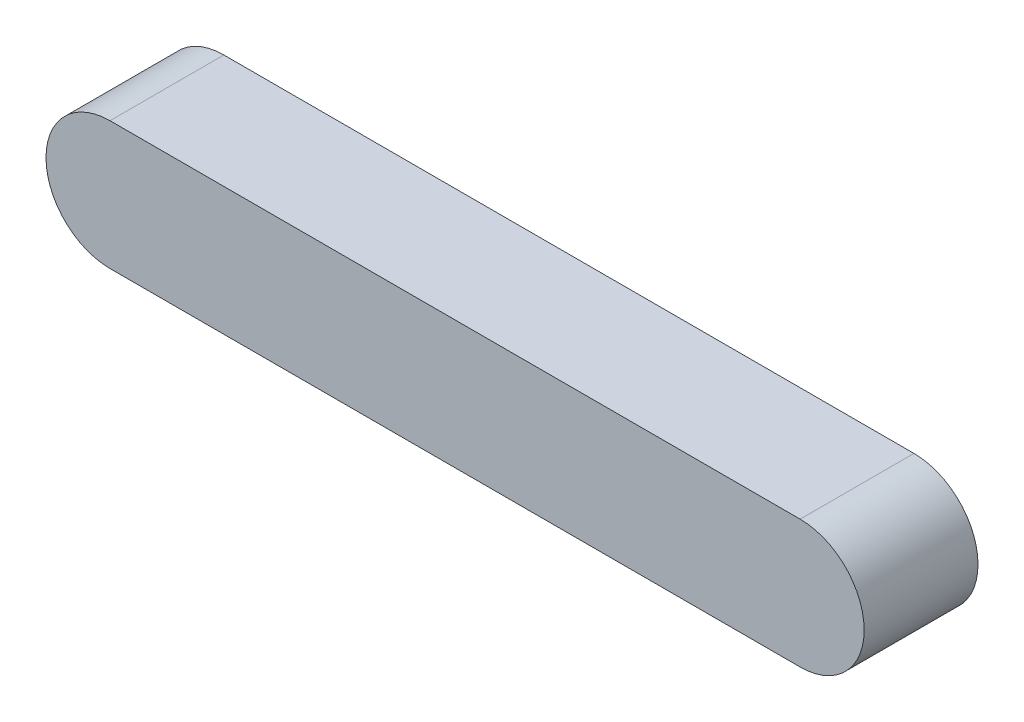
SolidWorks part; units mm, degrees
material "Plain Carbon Steel"
ref_plane "Front Plane" through (0, 0, 0) normal (0, 0, 1) x (1, 0, 0)
ref_plane "Top Plane" through (0, 0, 0) normal (0, 1, 0) x (1, 0, 0)
ref_plane "Right Plane" through (0, 0, 0) normal (1, 0, 0) x (0, 0, -1)
sketch "Sketch1" plane through (0, 0, 0) normal (0, 0, 1) x (1, 0, 0)
  line L0 (-48.5, 0) -> (48.5, 0) construction
  line L1 (-48.5, 9) -> (48.5, 9)
  line L2 (-48.5, -9) -> (48.5, -9)
  line L3 (-40.188, 0) -> (46.724, 0) construction
  line L4 (-57.5, 0) -> (-57.5, 16.5501) construction
  line L5 (57.5, 0) -> (57.5, 15.8403) construction
  arc A0 (-48.5, 9) -> (-48.5, -9) centre (-48.5, 0) ccw
  arc A1 (48.5, -9) -> (48.5, 9) centre (48.5, 0) ccw
  point P2 (0, 0)
  dimension "D2" = 9
  dimension "D1" = 115
extrude "Boss-Extrude1" add sketch "Sketch1" along normal blind 16
